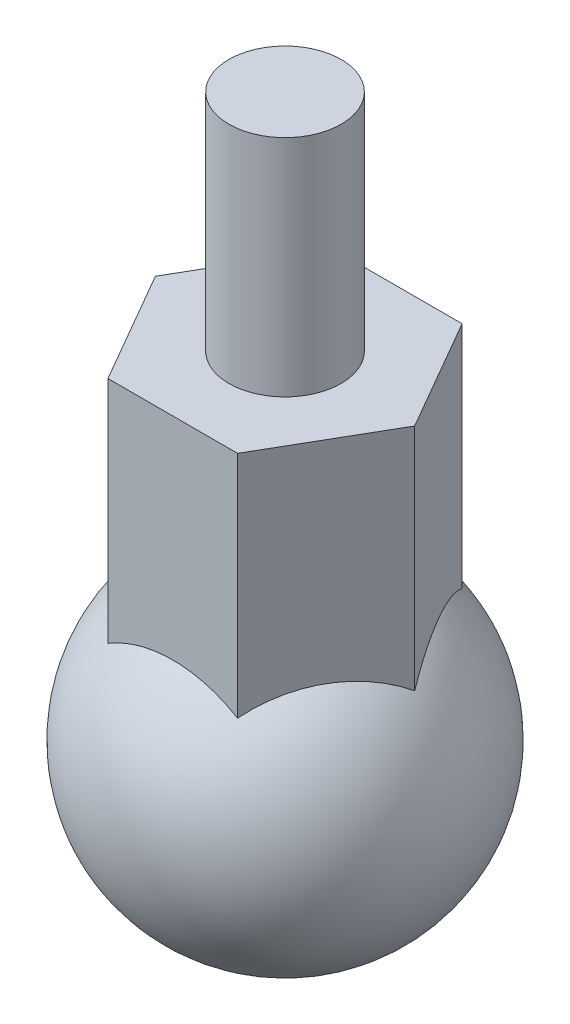
SolidWorks part; units mm, degrees
ref_plane "前视基准面" through (0, 0, 0) normal (0, 0, 1) x (1, 0, 0)
ref_plane "上视基准面" through (0, 0, 0) normal (0, 1, 0) x (1, 0, 0)
ref_plane "右视基准面" through (0, 0, 0) normal (1, 0, 0) x (0, 0, -1)
sketch "草图1" plane through (0, 0, 0) normal (0, 1, 0) x (1, 0, 0)
  line L0 (0, 3) -> (0, -3)
  arc A0 (0, -3) -> (0, 3) centre (0, 0) ccw
  dimension "D1" = 3
revolve "旋转1" add sketch "草图1" angle 360 about L0
sketch "草图2" plane through (0, 0, 0) normal (0, 1, 0) x (1, 0, 0)
  circle A0 centre (0, 0) radius 1
  dimension "D1" = 2
extrude "凸台-拉伸1" add sketch "草图2" along normal blind 10
sketch "草图3" plane through (0, 0, 0) normal (0, 1, 0) x (1, 0, 0)
  line L1 (2.3094, 0) -> (1.1547, 2)
  line L2 (1.1547, 2) -> (-1.1547, 2)
  line L3 (-1.1547, 2) -> (-2.3094, 0)
  line L4 (-2.3094, 0) -> (-1.1547, -2)
  line L5 (-1.1547, -2) -> (1.1547, -2)
  line L6 (1.1547, -2) -> (2.3094, 0)
  circle A0 centre (0, 0) radius 2 construction
  dimension "D1" = 4
extrude "凸台-拉伸2" add sketch "草图3" along normal blind 6
